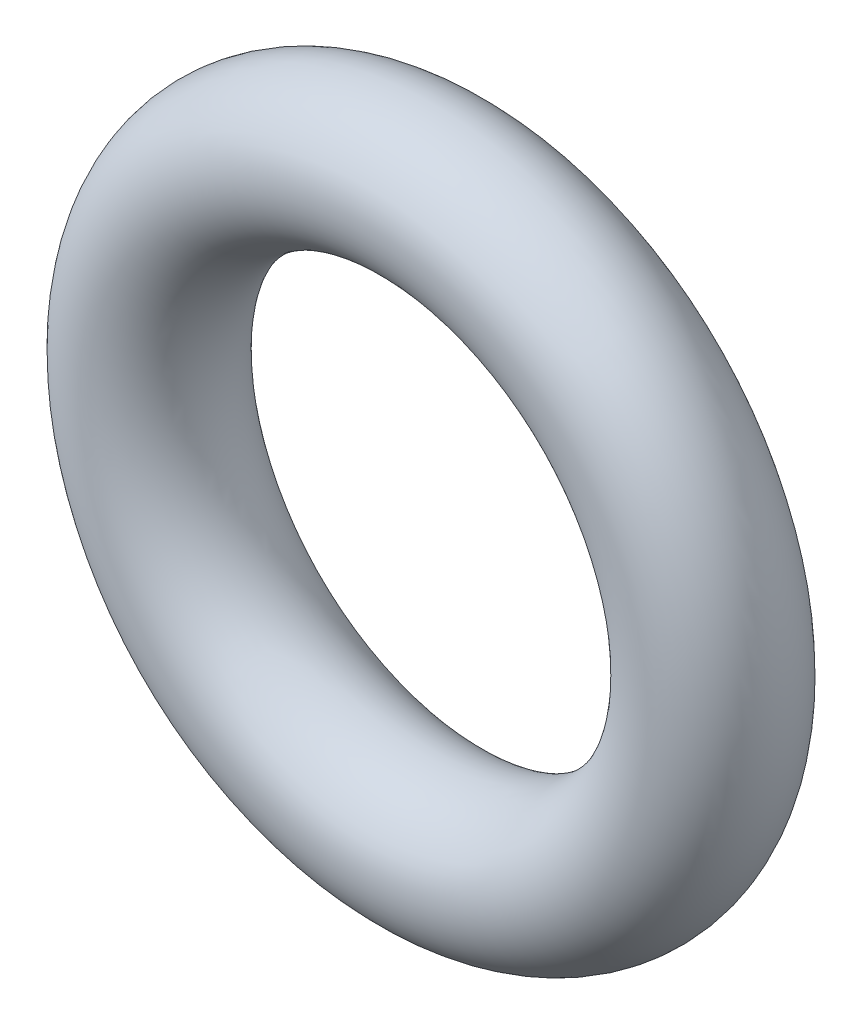
SolidWorks part; units mm, degrees
ref_plane "Front" through (0, 0, 0) normal (0, 0, 1) x (1, 0, 0)
ref_plane "Top" through (0, 0, 0) normal (0, 1, 0) x (1, 0, 0)
ref_plane "Right" through (0, 0, 0) normal (1, 0, 0) x (0, 0, -1)
sketch "Sketch1" plane through (0, 0, 0) normal (1, 0, 0) x (0, -1, 0)
  line L0 (0, -1.3081) -> (0, 1.3081) construction
  line L2 (-7.0548, 0) -> (7.0548, 0) construction
  line L3 (-3.7973, 0) -> (3.7973, 0) construction
  circle A0 centre (5.1054, 0) radius 1.3081
  point P9 (3.7973, 0)
  point P10 (6.4135, 0)
  point P13 (5.1054, 1.3081)
  point P14 (5.1054, -1.3081)
  dimension "Width" = 2.6162
  dimension "ID" = 7.5946
revolve "Revolve1" add sketch "Sketch1" angle 360 about L0
